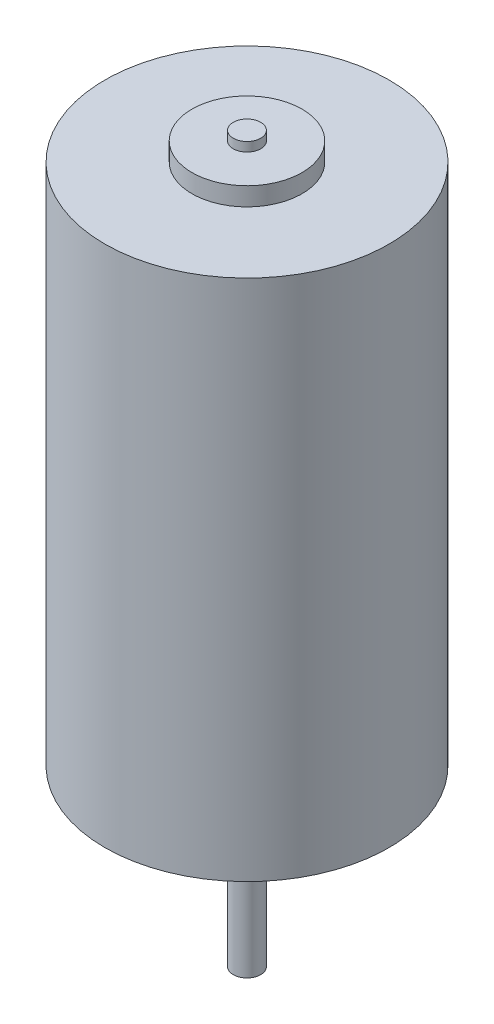
SolidWorks part; units mm, degrees
ref_plane "Plan de face" through (0, 0, 0) normal (0, 0, 1) x (1, 0, 0)
ref_plane "Plan de dessus" through (0, 0, 0) normal (0, 1, 0) x (1, 0, 0)
ref_plane "Plan de droite" through (0, 0, 0) normal (1, 0, 0) x (0, 0, -1)
sketch "Esquisse1" plane through (0, 0, 0) normal (0, 0, 1) x (1, 0, 0)
  line L0 (0, 0) -> (0, 72.0131) construction
  line L1 (0, -19) -> (0, 60)
  line L2 (0, 60) -> (1.5, 60)
  line L3 (1.5, 60) -> (1.5, 59)
  line L4 (1.5, 59) -> (6, 59)
  line L5 (6, 59) -> (6, 57)
  line L6 (6, 57) -> (15.5, 57)
  line L7 (15.5, 57) -> (15.5, 0)
  line L8 (15.5, 0) -> (6, 0)
  line L9 (1.5, -3.5) -> (1.5, -19)
  line L10 (1.5, -19) -> (0, -19)
  line L11 (1.5, -3.5) -> (6, -3.5)
  line L12 (6, -3.5) -> (6, 0)
  point P12 (0, 72.0131)
  dimension "D1" = 31
  dimension "D2" = 3
  dimension "D3" = 19
  dimension "D4" = 12
  dimension "D5" = 3.5
  dimension "D6" = 2
  dimension "D7" = 57
  dimension "D8" = 79
revolve "Révolution1" add sketch "Esquisse1" angle 360 about L0
hole_wizard "Trou taraudé M3x0.51" positions "Esquisse2" profile "Esquisse3" tap size "M3x0.5" standard "Ansi Metric"
sketch "Esquisse2" plane through (0, 0, 0) normal (0, -1, 0) x (-1, 0, 0)
  circle A0 centre (0, 0) radius 11 construction
  point P0 (0, -11)
  point P2 (-11, 0)
  point P4 (0, 11)
  point P6 (11, 0)
  point P13 (0, -27.3628)
  point P14 (-27.3628, 0)
  point P15 (0, 27.3628)
  point P16 (27.3628, 0)
  dimension "D1" = 22
sketch "Esquisse3" plane through (0, 0, 11) normal (1, 0, 0) x (0, 0, -1)
  line L0 (0, 0) -> (0, 9.2511)
  line L1 (0, 9.2511) -> (1.25, 8.5)
  line L2 (1.25, 8.5) -> (1.25, 0)
  line L5 (1.25, 0) -> (0, 0)
  line L10 (0, 9.2511) -> (-1.25, 8.5) construction
  line L11 (0, -6.35) -> (0, 107.95) construction
  dimension "Diamètre du trou pour taraudage" = 2.5
  dimension "Profondeur du trou pour taraudage" = 8.5
  dimension "Angle de pointe" = 118
cosmetic thread "Filetage de perçage1" parameters "D1"=6, "D2"=3
cosmetic thread "Filetage de perçage2" parameters "D1"=6, "D2"=3
cosmetic thread "Filetage de perçage3" parameters "D1"=6, "D2"=3
cosmetic thread "Filetage de perçage4" parameters "D1"=6, "D2"=3
